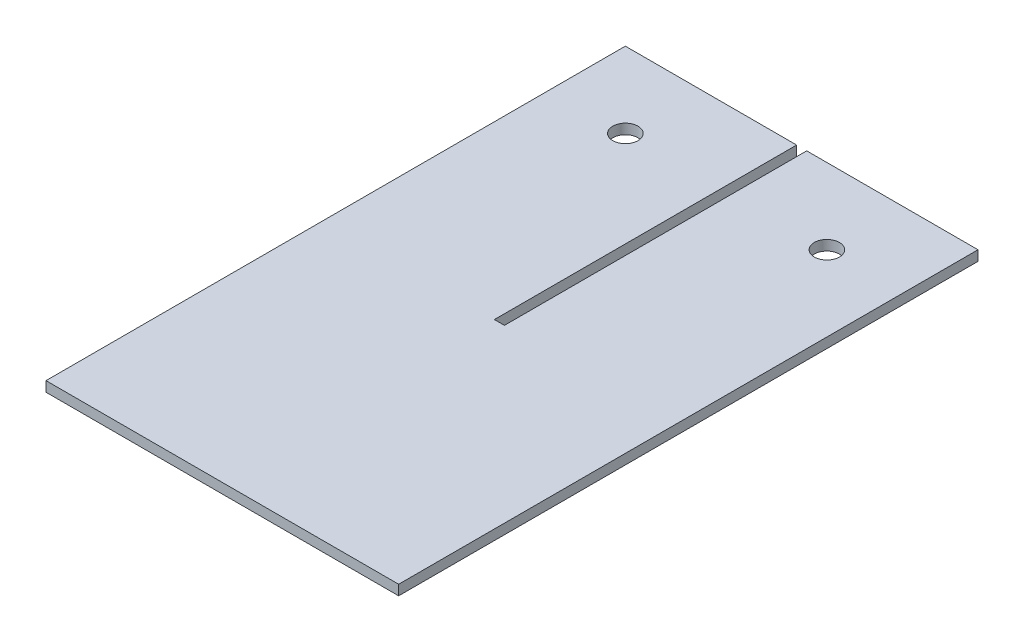
SolidWorks part; units mm, degrees
ref_plane "Front Plane" through (0, 0, 0) normal (0, 0, 1) x (1, 0, 0)
ref_plane "Top Plane" through (0, 0, 0) normal (0, 1, 0) x (1, 0, 0)
ref_plane "Right Plane" through (0, 0, 0) normal (1, 0, 0) x (0, 0, -1)
sketch "Sketch1" plane through (0, 0, 0) normal (0, 1, 0) x (1, 0, 0)
  line L0 (1, 57.5) -> (35, 57.5)
  line L1 (-35, 57.5) -> (-1, 57.5)
  line L2 (-35, 57.5) -> (-35, -57.5)
  line L3 (-35, -57.5) -> (35, -57.5)
  line L4 (35, 57.5) -> (35, -57.5)
  line L5 (-35, 57.5) -> (35, -57.5) construction
  line L6 (-35, -57.5) -> (35, 57.5) construction
  line L7 (1, -2.5) -> (-1, -2.5)
  line L8 (1, -2.5) -> (1, 57.5)
  line L10 (-1, -2.5) -> (-1, 57.5)
  line L11 (1, -2.5) -> (-1, 57.5) construction
  line L12 (1, 57.5) -> (-1, -2.5) construction
  line L13 (0, 27.5) -> (0, -60) construction
  circle A2 centre (-20, 42.5) radius 2.5
  circle A3 centre (20, 42.5) radius 2.5
  point P0 (0, 0)
  point P6 (0, 27.5)
  dimension "D6" = 15
  dimension "D8" = 5
  dimension "D9" = 5
  dimension "D1" = 70
  dimension "D2" = 115
  dimension "D3" = 2
  dimension "D4" = 34
  dimension "D5" = 60
  dimension "D7" = 15
  dimension "D10" = 15
  dimension "D11" = 15
extrude "Boss-Extrude1" add sketch "Sketch1" along normal blind 2
